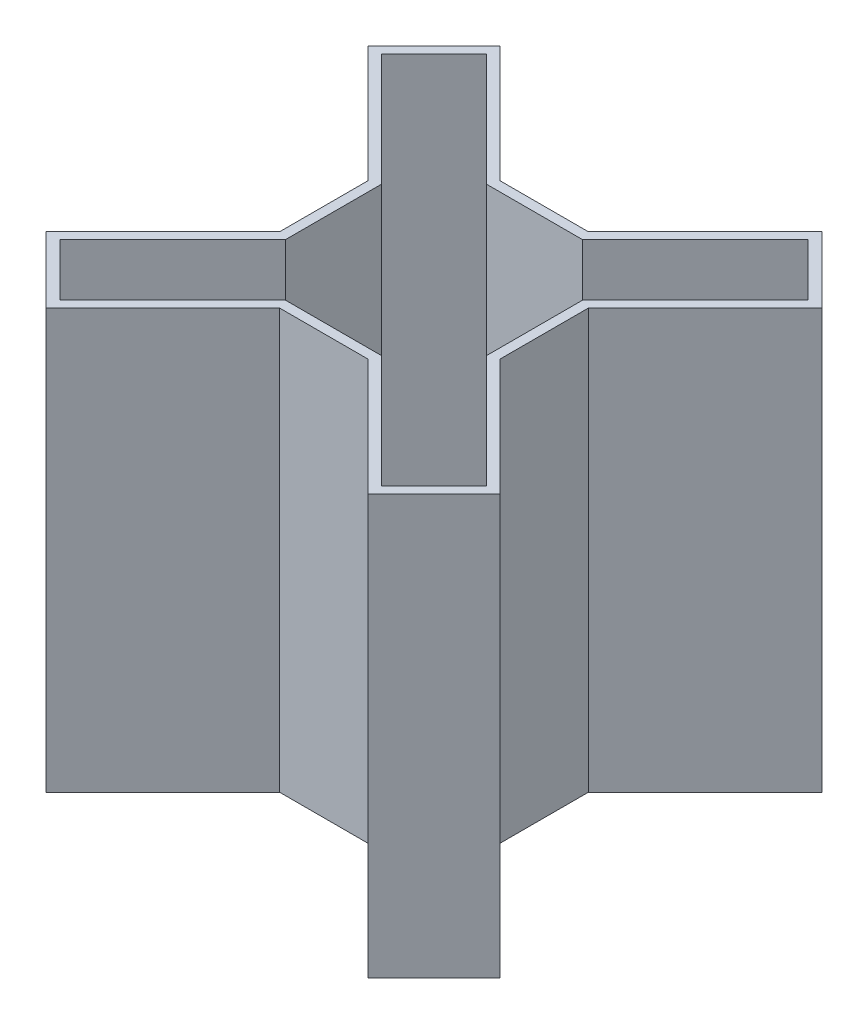
SolidWorks part; units mm, degrees
ref_plane "Front Plane" through (0, 0, 0) normal (0, 0, 1) x (1, 0, 0)
ref_plane "Top Plane" through (0, 0, 0) normal (0, 1, 0) x (1, 0, 0)
ref_plane "Right Plane" through (0, 0, 0) normal (1, 0, 0) x (0, 0, -1)
sketch "Sketch1" plane through (0, 0, 0) normal (0, 1, 0) x (1, 0, 0)
  line L0 (-50.0474, -102.3043) -> (48.5642, -102.3043)
  line L1 (-103.7875, -48.5642) -> (-103.7875, 50.0474)
  line L2 (-50.0474, 103.7875) -> (48.5642, 103.7875)
  line L3 (102.3043, -48.5642) -> (102.3043, 50.0474)
  line L4 (164.1535, 219.3768) -> (217.8936, 165.6367)
  line L5 (217.8936, -164.1535) -> (164.1535, -217.8936)
  line L6 (-165.6367, -217.8936) -> (-219.3768, -164.1535)
  line L7 (102.3043, 50.0474) -> (217.8936, 165.6367)
  line L8 (-219.3768, 165.6367) -> (-165.6367, 219.3768)
  line L9 (102.3043, -48.5642) -> (217.8936, -164.1535)
  line L10 (48.5642, -102.3043) -> (164.1535, -217.8936)
  line L11 (-50.0474, -102.3043) -> (-165.6367, -217.8936)
  line L12 (-103.7875, -48.5642) -> (-219.3768, -164.1535)
  line L13 (-103.7875, 50.0474) -> (-219.3768, 165.6367)
  line L14 (-50.0474, 103.7875) -> (-165.6367, 219.3768)
  line L15 (48.5642, 103.7875) -> (164.1535, 219.3768)
  line L16 (-113.7875, 45.9053) -> (-233.5189, 165.6367)
  line L17 (-233.5189, 165.6367) -> (-165.6367, 233.5189)
  line L18 (-45.9053, 113.7875) -> (-165.6367, 233.5189)
  line L19 (-45.9053, 113.7875) -> (44.4221, 113.7875)
  line L20 (44.4221, 113.7875) -> (164.1535, 233.5189)
  line L21 (164.1535, 233.5189) -> (232.0357, 165.6367)
  line L22 (112.3043, 45.9053) -> (232.0357, 165.6367)
  line L23 (112.3043, -44.4221) -> (112.3043, 45.9053)
  line L24 (112.3043, -44.4221) -> (232.0357, -164.1535)
  line L25 (232.0357, -164.1535) -> (164.1535, -232.0357)
  line L26 (44.4221, -112.3043) -> (164.1535, -232.0357)
  line L27 (-45.9053, -112.3043) -> (44.4221, -112.3043)
  line L28 (-45.9053, -112.3043) -> (-165.6367, -232.0357)
  line L29 (-165.6367, -232.0357) -> (-233.5189, -164.1535)
  line L30 (-113.7875, -44.4221) -> (-233.5189, -164.1535)
  line L31 (-113.7875, -44.4221) -> (-113.7875, 45.9053)
  point P0 (-0.7416, 0.7416)
  point P8 (-0.7416, 0.7416)
  point P17 (-0.7416, 0.7416)
  dimension "D1" = 10
extrude "Boss-Extrude1" add sketch "Sketch1" against normal blind 420
sketch "Sketch3" plane through (0, -420, 0) normal (0, -1, 0) x (1, 0, 0)
  line L32 (-113.7875, 44.4221) -> (-113.7875, -45.9053)
  line L33 (-113.7875, -45.9053) -> (-233.5189, -165.6367)
  line L34 (-233.5189, -165.6367) -> (-165.6367, -233.5189)
  line L35 (-165.6367, -233.5189) -> (-45.9053, -113.7875)
  line L36 (-45.9053, -113.7875) -> (44.4221, -113.7875)
  line L37 (44.4221, -113.7875) -> (164.1535, -233.5189)
  line L38 (164.1535, -233.5189) -> (232.0357, -165.6367)
  line L39 (232.0357, -165.6367) -> (112.3043, -45.9053)
  line L40 (112.3043, -45.9053) -> (112.3043, 44.4221)
  line L41 (112.3043, 44.4221) -> (232.0357, 164.1535)
  line L42 (232.0357, 164.1535) -> (164.1535, 232.0357)
  line L43 (164.1535, 232.0357) -> (44.4221, 112.3043)
  line L44 (44.4221, 112.3043) -> (-45.9053, 112.3043)
  line L45 (-45.9053, 112.3043) -> (-165.6367, 232.0357)
  line L46 (-165.6367, 232.0357) -> (-233.5189, 164.1535)
  line L47 (-233.5189, 164.1535) -> (-113.7875, 44.4221)
  line L48 (-113.7875, 44.4221) -> (-113.7875, -45.9053)
  line L49 (-113.7875, -45.9053) -> (-233.5189, -165.6367)
  line L50 (-233.5189, -165.6367) -> (-165.6367, -233.5189)
  line L51 (-165.6367, -233.5189) -> (-45.9053, -113.7875)
  line L52 (-45.9053, -113.7875) -> (44.4221, -113.7875)
  line L53 (44.4221, -113.7875) -> (164.1535, -233.5189)
  line L54 (164.1535, -233.5189) -> (232.0357, -165.6367)
  line L55 (232.0357, -165.6367) -> (112.3043, -45.9053)
  line L56 (112.3043, -45.9053) -> (112.3043, 44.4221)
  line L57 (112.3043, 44.4221) -> (232.0357, 164.1535)
  line L58 (232.0357, 164.1535) -> (164.1535, 232.0357)
  line L59 (164.1535, 232.0357) -> (44.4221, 112.3043)
  line L60 (44.4221, 112.3043) -> (-45.9053, 112.3043)
  line L61 (-45.9053, 112.3043) -> (-165.6367, 232.0357)
  line L62 (-165.6367, 232.0357) -> (-233.5189, 164.1535)
  line L63 (-233.5189, 164.1535) -> (-113.7875, 44.4221)
  dimension "D1" = 0
extrude "Boss-Extrude2" add sketch "Sketch3" along normal blind 10
